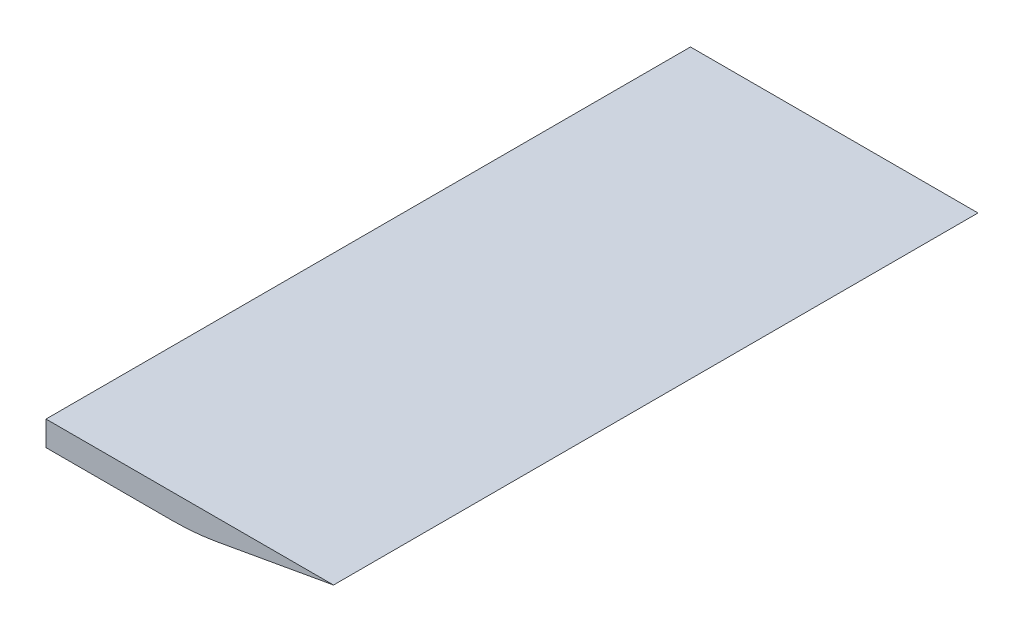
SolidWorks part; units mm, degrees
ref_plane "Front Plane" through (0, 0, 0) normal (0, 0, 1) x (1, 0, 0)
ref_plane "Top Plane" through (0, 0, 0) normal (0, 1, 0) x (1, 0, 0)
ref_plane "Right Plane" through (0, 0, 0) normal (1, 0, 0) x (0, 0, -1)
sketch "Sketch1" plane through (0, 0, 0) normal (0, 0, 1) x (1, 0, 0)
  line L0 (0, 0) -> (58, 0)
  line L1 (58, 0) -> (30, -5)
  line L2 (30, -5) -> (0, -5)
  line L3 (0, -5) -> (0, 0)
  dimension "D1" = 5
  dimension "D2" = 28
  dimension "D3" = 30
extrude "Boss-Extrude1" add sketch "Sketch1" along normal blind 130
fillet "Fillet1" radius 50 1 edges at (30, -5, 65)
